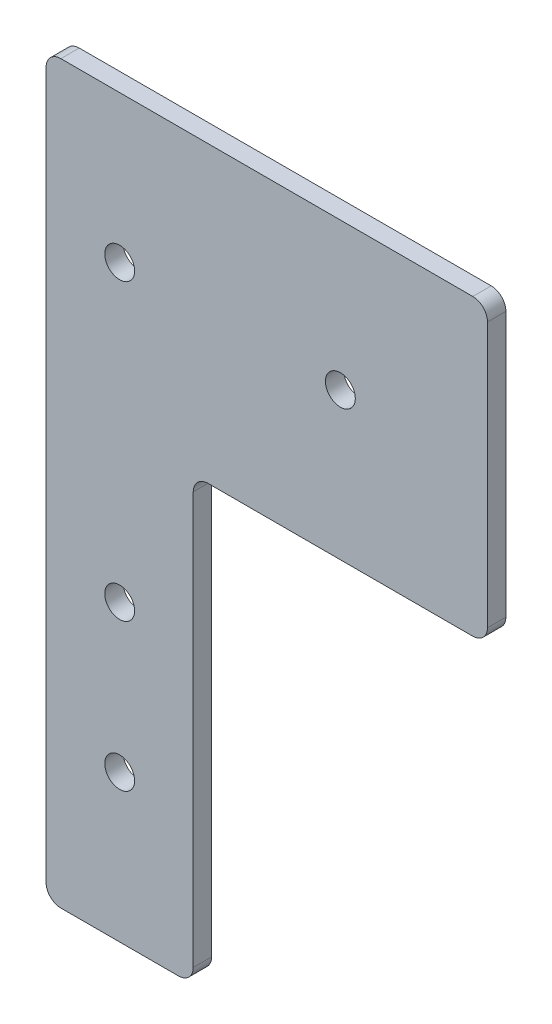
SolidWorks part; units mm, degrees
material "5052-O"
ref_plane "Front Plane" through (0, 0, 0) normal (0, 0, 1) x (1, 0, 0)
ref_plane "Top Plane" through (0, 0, 0) normal (0, 1, 0) x (1, 0, 0)
ref_plane "Right Plane" through (0, 0, 0) normal (1, 0, 0) x (0, 0, -1)
sketch "Sketch1" plane through (0, 0, 0) normal (0, 0, 1) x (1, 0, 0)
  line L0 (12.7, 63.5) -> (12.7, 12.7) construction
  line L1 (-12.7, -63.5) -> (12.7, -63.5)
  line L2 (-12.7, -63.5) -> (-12.7, 63.5)
  line L3 (-12.7, 63.5) -> (12.7, 63.5)
  line L4 (12.7, -63.5) -> (12.7, 12.7)
  line L5 (-12.7, -63.5) -> (12.7, 63.5) construction
  line L6 (-12.7, 63.5) -> (12.7, -63.5) construction
  line L7 (12.7, 63.5) -> (63.5, 63.5)
  line L9 (12.7, 12.7) -> (63.5, 12.7)
  line L10 (63.5, 63.5) -> (63.5, 12.7)
  point P0 (0, 0)
  dimension "D1" = 25.4
  dimension "D2" = 127
  dimension "D3" = 50.8
  dimension "D4" = 50.8
extrude "Boss-Extrude1" add sketch "Sketch1" along normal blind 3.175
sketch "Sketch2" plane through (0, 0, 3.175) normal (0, 0, 1) x (1, 0, 0)
  line L0 (63.5, 38.1) -> (-12.7, 38.1) construction
  line L1 (63.5, 12.7) -> (63.5, 63.5) construction
  line L2 (-12.7, 63.5) -> (-12.7, -63.5) construction
  line L3 (0, -63.5) -> (0, 63.5) construction
  line L4 (-12.7, -63.5) -> (12.7, -63.5) construction
  line L5 (63.5, 63.5) -> (-12.7, 63.5) construction
  line L6 (38.1, 12.7) -> (38.1, 63.5) construction
  line L7 (12.7, 12.7) -> (63.5, 12.7) construction
  circle A0 centre (0, 38.1) radius 2.5797
  circle A1 centre (38.1, 38.1) radius 2.5797
  circle A2 centre (0, -38.1) radius 2.5797
  circle A3 centre (0, -12.7) radius 2.5797
  dimension "D1" = 5.1594
  dimension "D2" = 25.4
  dimension "D3" = 25.4
extrude "Cut-Extrude1" cut sketch "Sketch2" against normal blind 3.175
fillet "Fillet1" radius 2.54 6 edges at (-12.7, 63.5, 1.5875) (-12.7, -63.5, 1.5875) (12.7, -63.5, 1.5875) (12.7, 12.7, 1.5875) (63.5, 12.7, 1.5875) (63.5, 63.5, 1.5875)
